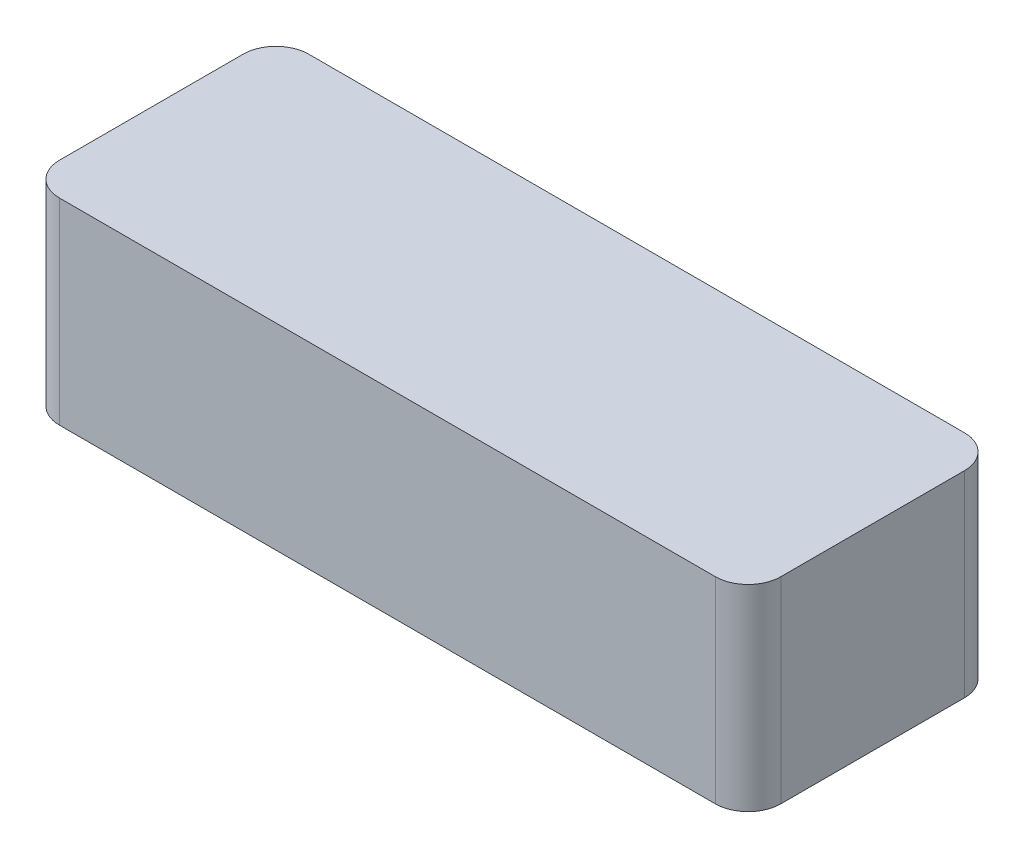
SolidWorks part; units mm, degrees
material "Custom Plastic"
ref_plane "Front Plane" through (0, 0, 0) normal (0, 0, 1) x (1, 0, 0)
ref_plane "Top Plane" through (0, 0, 0) normal (0, 1, 0) x (1, 0, 0)
ref_plane "Right Plane" through (0, 0, 0) normal (1, 0, 0) x (0, 0, -1)
sketch "Sketch1" plane through (0, 0, 0) normal (0, 1, 0) x (1, 0, 0)
  line L1 (-41.8004, -14.4857) -> (58.1996, -14.4857)
  line L2 (-46.8004, -9.4857) -> (-46.8004, 18.5143)
  line L3 (-41.8004, 23.5143) -> (58.1996, 23.5143)
  line L4 (63.1996, -9.4857) -> (63.1996, 18.5143)
  arc A0 (-41.8004, -14.4857) -> (-46.8004, -9.4857) centre (-41.8004, -9.4857) cw
  arc A1 (58.1996, -14.4857) -> (63.1996, -9.4857) centre (58.1996, -9.4857) ccw
  arc A2 (58.1996, 23.5143) -> (63.1996, 18.5143) centre (58.1996, 18.5143) cw
  arc A3 (-46.8004, 18.5143) -> (-41.8004, 23.5143) centre (-41.8004, 18.5143) cw
  dimension "D1" = 5
  dimension "D2" = 110
  dimension "D3" = 38
extrude "Boss-Extrude1" add sketch "Sketch1" along normal blind 30
